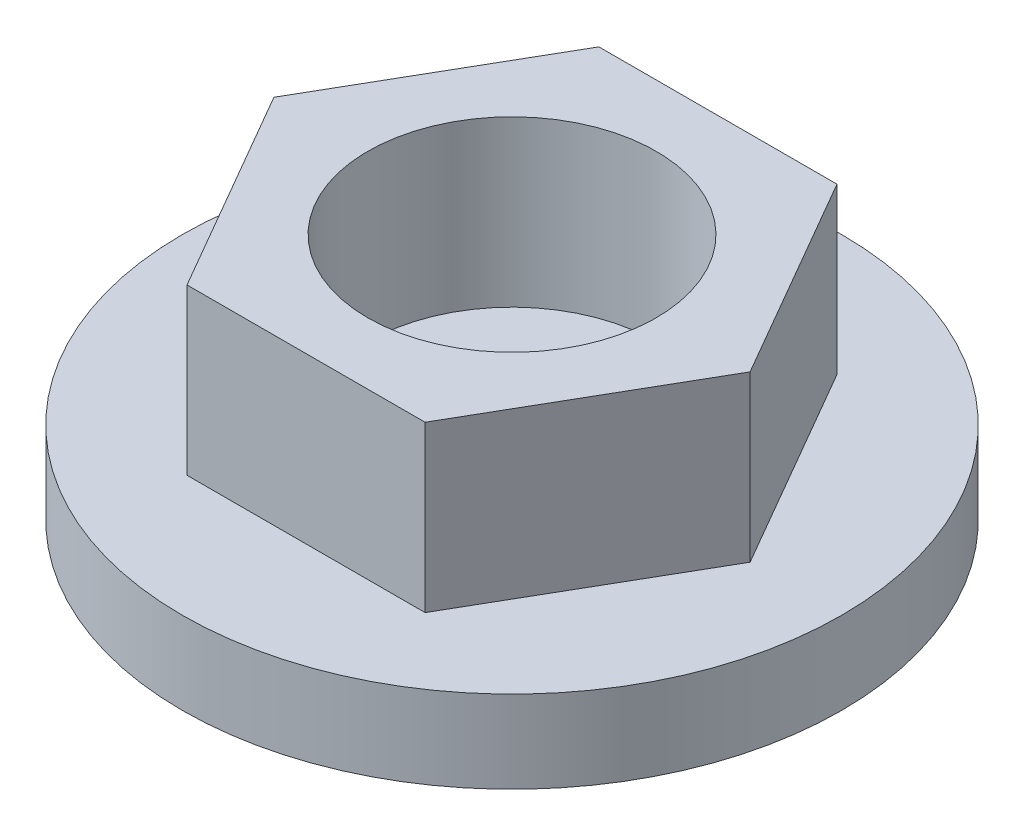
SolidWorks part; units mm, degrees
ref_plane "Alzado" through (0, 0, 0) normal (0, 0, 1) x (1, 0, 0)
ref_plane "Planta" through (0, 0, 0) normal (0, 1, 0) x (1, 0, 0)
ref_plane "Vista lateral" through (0, 0, 0) normal (1, 0, 0) x (0, 0, -1)
sketch "Croquis1" plane through (0, 0, 0) normal (0, 1, 0) x (1, 0, 0)
  circle A0 centre (0, 0) radius 4
  dimension "D1" = 8
extrude "Saliente-Extruir2" add sketch "Croquis1" along normal blind 1
sketch "Croquis2" plane through (0, 1, 0) normal (0, 1, 0) x (1, 0, 0)
  line L1 (1.4419, 2.5008) -> (-1.4448, 2.4992)
  line L2 (-1.4448, 2.4992) -> (-2.8868, -0.0017)
  line L3 (-2.8868, -0.0017) -> (-1.4419, -2.5008)
  line L4 (-1.4419, -2.5008) -> (1.4448, -2.4992)
  line L5 (1.4448, -2.4992) -> (2.8868, 0.0017)
  line L6 (2.8868, 0.0017) -> (1.4419, 2.5008)
  circle A0 centre (0, 0) radius 2.5 construction
  circle A1 centre (0, 0) radius 1.75
  dimension "D2" = 3.5
  dimension "D1" = 5
extrude "Saliente-Extruir3" add sketch "Croquis2" along normal blind 2
